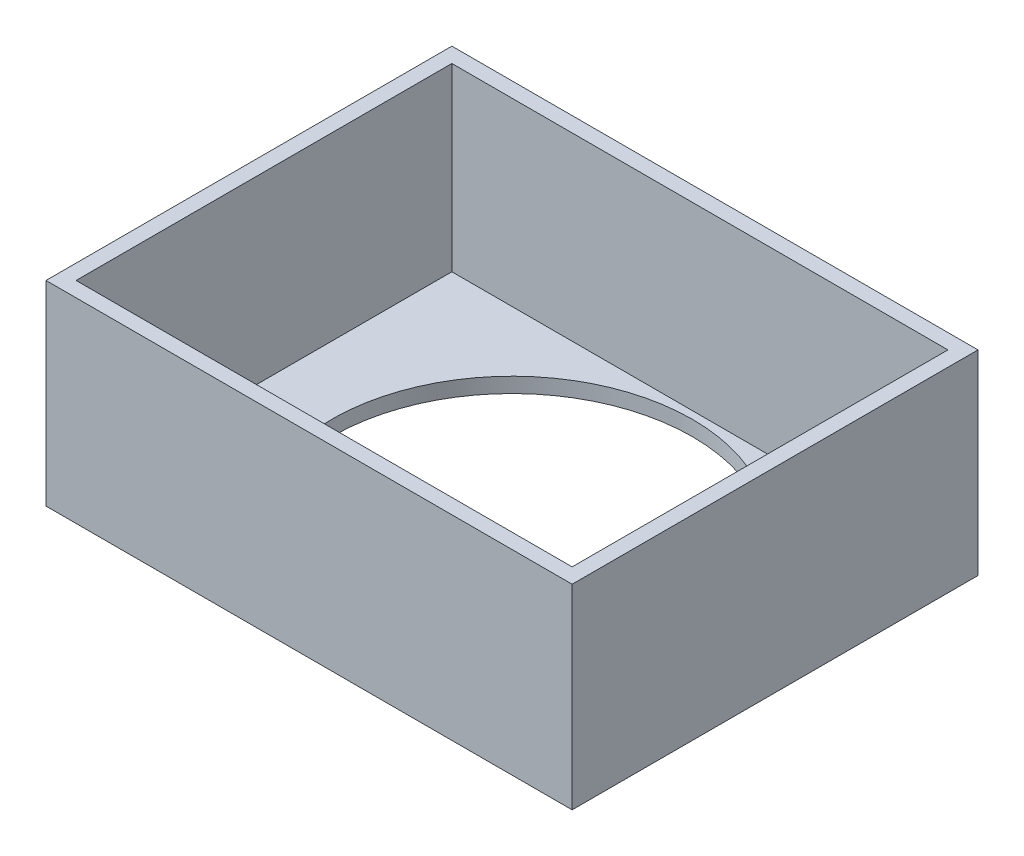
SolidWorks part; units mm, degrees
ref_plane "정면" through (0, 0, 0) normal (0, 0, 1) x (1, 0, 0)
ref_plane "윗면" through (0, 0, 0) normal (0, 1, 0) x (1, 0, 0)
ref_plane "우측면" through (0, 0, 0) normal (1, 0, 0) x (0, 0, -1)
sketch "스케치1" plane through (0, 0, 0) normal (0, 1, 0) x (1, 0, 0)
  line L1 (17.5, -13.5) -> (-17.5, -13.5)
  line L2 (17.5, -13.5) -> (17.5, 13.5)
  line L3 (17.5, 13.5) -> (-17.5, 13.5)
  line L4 (-17.5, -13.5) -> (-17.5, 13.5)
  line L5 (17.5, -13.5) -> (-17.5, 13.5) construction
  line L6 (17.5, 13.5) -> (-17.5, -13.5) construction
  point P0 (0, 0)
  dimension "D1" = 35
  dimension "D2" = 27
extrude "보스-돌출1" add sketch "스케치1" along normal blind 13
sketch "스케치2" plane through (0, 0, 0) normal (0, 1, 0) x (1, 0, 0)
  line L0 (-17.5, 13.5) -> (-17.5, -13.5) construction
  line L1 (-16.5, 12.5) -> (16.5, 12.5)
  line L2 (-16.5, 12.5) -> (-16.5, -12.5)
  line L3 (-16.5, -12.5) -> (16.5, -12.5)
  line L4 (16.5, 12.5) -> (16.5, -12.5)
  line L5 (17.5, 13.5) -> (-17.5, 13.5) construction
  dimension "D1" = 33
  dimension "D2" = 25
  dimension "D3" = 1
  dimension "D4" = 1
extrude "컷-돌출1" cut sketch "스케치2" along normal blind 15 from offset 1
sketch "스케치3" plane through (0, 0, 0) normal (0, 1, 0) x (1, 0, 0)
  circle A0 centre (0, 0) radius 12
  dimension "D1" = 24
extrude "컷-돌출2" cut sketch "스케치3" along normal through all
